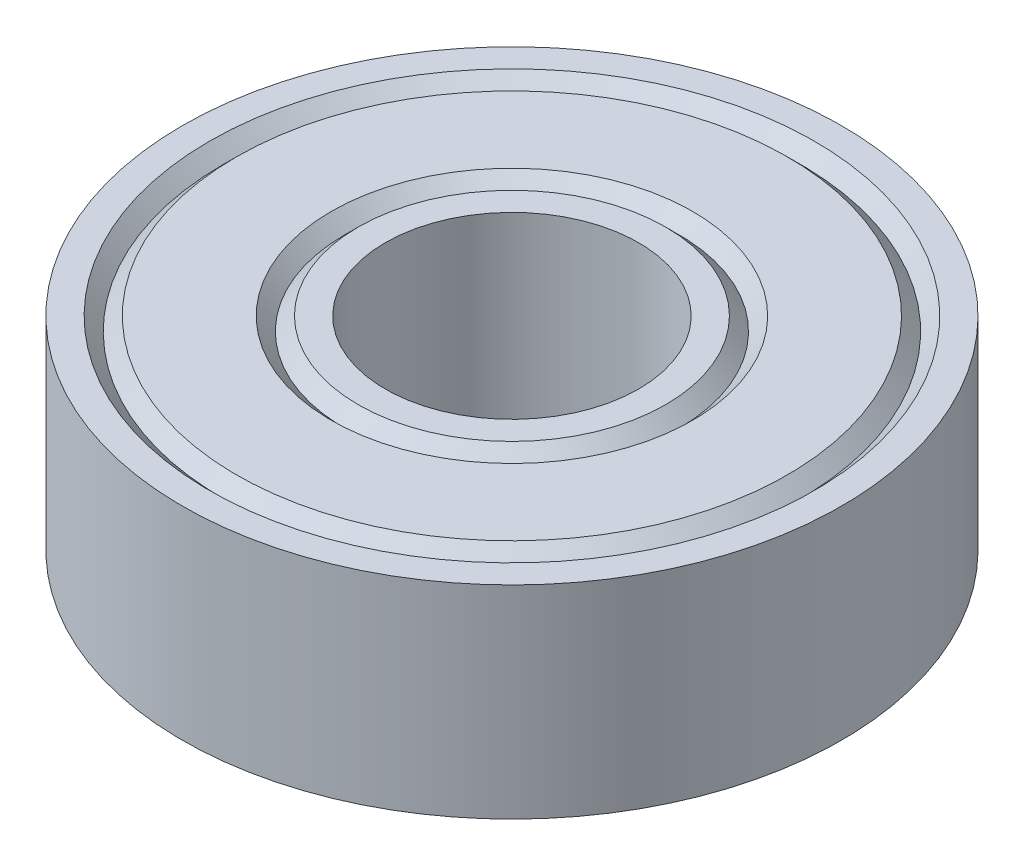
SolidWorks part; units mm, degrees
ref_plane "Front Plane" through (0, 0, 0) normal (0, 0, 1) x (1, 0, 0)
ref_plane "Top Plane" through (0, 0, 0) normal (0, 1, 0) x (1, 0, 0)
ref_plane "Right Plane" through (0, 0, 0) normal (1, 0, 0) x (0, 0, -1)
sketch "Sketch1" plane through (0, 0, 0) normal (0, 0, 1) x (1, 0, 0)
  line L0 (0, 2) -> (0, -2) construction
  line L1 (-2.5, 2) -> (-3.0333, 2)
  line L2 (-2.5, 2) -> (-2.5, -2)
  line L3 (-2.5, -2) -> (-3.0333, -2)
  line L4 (-6.5, 2) -> (-6.5, -2)
  line L5 (-5.9667, 2) -> (-5.7, 1.7333)
  line L6 (-5.7, 1.7333) -> (-5.4333, 2)
  line L7 (-3.5667, 2) -> (-3.3, 1.7333)
  line L8 (-3.3, 1.7333) -> (-3.0333, 2)
  line L9 (-5.9667, -2) -> (-5.7, -1.7333)
  line L10 (-5.7, -1.7333) -> (-5.4333, -2)
  line L11 (-3.5667, -2) -> (-3.3, -1.7333)
  line L12 (-3.3, -1.7333) -> (-3.0333, -2)
  line L13 (-3.5667, -2) -> (-5.4333, -2)
  line L14 (-5.9667, -2) -> (-6.5, -2)
  line L15 (-5.9667, 2) -> (-6.5, 2)
  line L16 (-3.5667, 2) -> (-5.4333, 2)
  line L17 (-5.7, 1.7333) -> (-3.3, 1.7333) construction
  line L18 (-5.7, 1.7333) -> (-5.7, -1.7333) construction
  line L19 (-3.3, -1.7333) -> (-5.7, -1.7333) construction
  line L20 (-3.3, 1.7333) -> (-3.3, -1.7333) construction
  line L21 (-5.7, 0) -> (-4.9, 0) construction
  line L22 (-3.0333, 2) -> (-3.5667, 2) construction
  line L23 (-4.9, 0) -> (-4.1, 0) construction
  line L24 (-5.7, 0) -> (-6.5, 0) construction
  line L25 (-4.1, 0) -> (-3.3, 0) construction
  line L26 (-3.3, 0) -> (-2.5, 0) construction
  dimension "D1" = 4
  dimension "D2" = 5
  dimension "D3" = 13
revolve "Revolve1" add sketch "Sketch1" angle 360 about L0
